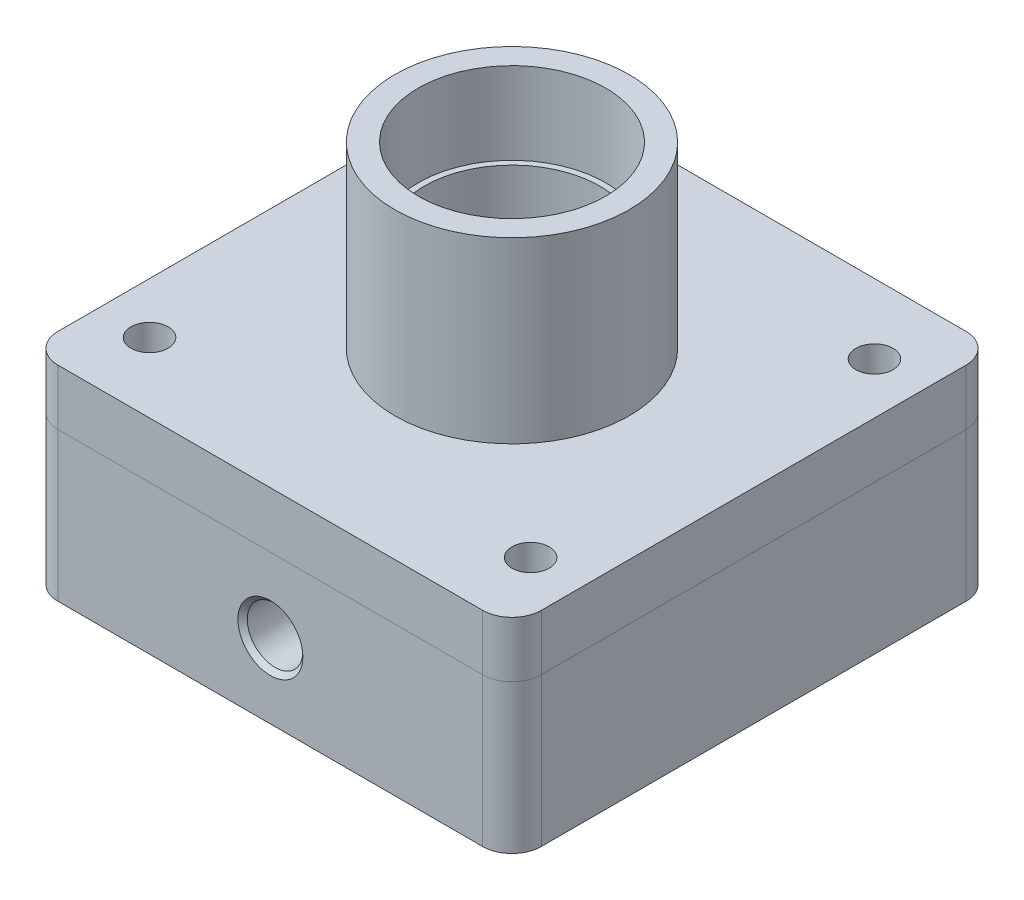
SolidWorks part; units mm, degrees
ref_plane "Front Plane" through (0, 0, 0) normal (0, 0, 1) x (1, 0, 0)
ref_plane "Top Plane" through (0, 0, 0) normal (0, 1, 0) x (1, 0, 0)
ref_plane "Right Plane" through (0, 0, 0) normal (1, 0, 0) x (0, 0, -1)
sketch "Sketch1" plane through (0, 0, 0) normal (0, 1, 0) x (1, 0, 0)
  line L1 (-82.5, 82.5) -> (82.5, 82.5)
  line L2 (-82.5, 82.5) -> (-82.5, -82.5)
  line L3 (-82.5, -82.5) -> (82.5, -82.5)
  line L4 (82.5, 82.5) -> (82.5, -82.5)
  line L5 (-82.5, 82.5) -> (82.5, -82.5) construction
  line L6 (-82.5, -82.5) -> (82.5, 82.5) construction
  point P0 (0, 0)
extrude "Boss-Extrude1" add sketch "Sketch1" along normal blind 50.8
sketch "Sketch2" plane through (0, 50.8, 0) normal (0, 1, 0) x (1, 0, 0)
  circle A0 centre (0, 0) radius 40
extrude "Boss-Extrude2" add sketch "Sketch2" along normal blind 80
sketch "Sketch3" plane through (0, 130.8, 0) normal (0, 1, 0) x (1, 0, 0)
  circle A0 centre (0, 0) radius 32
extrude "Cut-Extrude1" cut sketch "Sketch3" against normal blind 28
sketch "Sketch4" plane through (0, 102.8, 0) normal (0, 1, 0) x (1, 0, 0)
  circle A0 centre (0, 0) radius 30
extrude "Cut-Extrude2" cut sketch "Sketch4" against normal blind 22
fillet "Fillet1" radius 10 4 edges at (82.5, 25.4, 82.5) (-82.5, 25.4, -82.5) (82.5, 25.4, -82.5) (-82.5, 25.4, 82.5)
sketch "Sketch5" plane through (0, 0, 0) normal (0, -1, 0) x (1, 0, 0)
  circle A0 centre (0, 0) radius 20
extrude "Cut-Extrude3" cut sketch "Sketch5" against normal blind 40
sketch "Sketch6" plane through (0, 0, 0) normal (0, -1, 0) x (1, 0, 0)
  circle A0 centre (0, 0) radius 76.2
  circle A1 centre (0, 0) radius 69.85
extrude "Cut-Extrude4" cut sketch "Sketch6" against normal blind 10
sketch "Sketch7" plane through (0, 0, 82.5) normal (0, 0, 1) x (1, 0, 0)
  line L0 (-72.5, 25.4) -> (76.5172, 25.4) construction
  line L1 (-72.5, 50.8) -> (-72.5, 0) construction
sketch "Sketch12" plane through (0, 0, 0) normal (0, -1, 0) x (1, 0, 0)
  line L0 (0, 50.5) -> (0, 82.5)
  line L1 (-72.5, 82.5) -> (76.5172, 82.5) construction
  line L2 (0, 0) -> (0, 50.5)
  circle A0 centre (0, 50.5) radius 6.35
  dimension "D1" = 32
sketch "Sketch16" plane through (0, 0, 82.5) normal (0, 0, 1) x (1, 0, 0)
  line L0 (0, 0) -> (0, 50.8) construction
  line L1 (-72.5, 50.8) -> (72.5, 50.8) construction
hole_wizard "1/2-14 NPSM Tapped Hole2" positions "Sketch18" profile "Sketch19" tap size "1/2-14 NPSM" standard "ANSI Inch"
sketch "Sketch18" plane through (0, 0, 82.5) normal (0, 0, 1) x (1, 0, 0)
  line L0 (0, 0) -> (0, 50.8) construction
  point P0 (0, 25.4)
sketch "Sketch19" plane through (0, 25.4, 82.5) normal (1, 0, 0) x (0, -1, 0)
  line L0 (0, 0) -> (0, 52.9503)
  line L1 (0, 52.9503) -> (9.4869, 47.25)
  line L2 (9.4869, 47.25) -> (9.4869, 1.6002)
  line L3 (9.4869, 1.6002) -> (11.0871, 0)
  line L5 (11.0871, 0) -> (0, 0)
  line L6 (-9.4869, 1.6002) -> (-11.0871, 0) construction
  line L10 (0, 52.9503) -> (-9.4869, 47.25) construction
  line L11 (0, -6.35) -> (0, 107.95) construction
  dimension "Tap Drill Dia." = 18.9738
  dimension "Tap Drill Depth" = 47.25
  dimension "Near C'Sink Dia." = 22.1742
  dimension "Near C'Sink Angle" = 90
  dimension "Drill Angle" = 118
cosmetic thread "Hole Thread2" parameters "D1"=41.81, "D2"=20.9042
extrude "Cut-Extrude5" cut sketch "Sketch12" against normal blind 25 contours A0
sketch "Sketch20" plane through (0, 0, 0) normal (0, -1, 0) x (1, 0, 0)
  line L1 (-65.0558, 58.7091) -> (65.0558, 58.7091) construction
  line L2 (-65.0558, 58.7091) -> (-65.0558, -58.7091) construction
  line L3 (-65.0558, -58.7091) -> (65.0558, -58.7091) construction
  line L4 (65.0558, 58.7091) -> (65.0558, -58.7091) construction
  line L5 (-65.0558, 58.7091) -> (65.0558, -58.7091) construction
  line L6 (-65.0558, -58.7091) -> (65.0558, 58.7091) construction
  circle A0 centre (0, 0) radius 87.63
  circle A1 centre (-65.0558, 58.7091) radius 6.35
  circle A2 centre (-65.0558, -58.7091) radius 6.35
  circle A3 centre (65.0558, -58.7091) radius 6.35
  circle A4 centre (65.0558, 58.7091) radius 6.35
extrude "Cut-Extrude6" cut sketch "Sketch20" against normal through all contours A1 | A3 | A2 | A4
sketch "Sketch24" plane through (0, 50.8, 0) normal (0, 1, 0) x (1, 0, 0)
  line L4 (-72.5, -82.5) -> (72.5, -82.5)
  line L5 (82.5, -72.5) -> (82.5, 72.5)
  line L6 (72.5, 82.5) -> (-72.5, 82.5)
  line L7 (-82.5, 72.5) -> (-82.5, -72.5)
  line L8 (-72.5, -82.5) -> (72.5, -82.5)
  line L9 (82.5, -72.5) -> (82.5, 72.5)
  line L10 (72.5, 82.5) -> (-72.5, 82.5)
  line L11 (-82.5, 72.5) -> (-82.5, -72.5)
  circle A0 centre (-65.0558, -58.7091) radius 6.35 construction
  circle A1 centre (-65.0558, 58.7091) radius 6.35 construction
  circle A2 centre (65.0558, -58.7091) radius 6.35 construction
  circle A3 centre (65.0558, 58.7091) radius 6.35 construction
  arc A4 (72.5, -82.5) -> (82.5, -72.5) centre (72.5, -72.5) ccw
  arc A5 (82.5, 72.5) -> (72.5, 82.5) centre (72.5, 72.5) ccw
  arc A6 (-72.5, 82.5) -> (-82.5, 72.5) centre (-72.5, 72.5) ccw
  arc A7 (-82.5, -72.5) -> (-72.5, -82.5) centre (-72.5, -72.5) ccw
  arc A8 (72.5, -82.5) -> (82.5, -72.5) centre (72.5, -72.5) ccw
  arc A9 (82.5, 72.5) -> (72.5, 82.5) centre (72.5, 72.5) ccw
  arc A10 (-72.5, 82.5) -> (-82.5, 72.5) centre (-72.5, 72.5) ccw
  arc A11 (-82.5, -72.5) -> (-72.5, -82.5) centre (-72.5, -72.5) ccw
  circle A12 centre (-65.0558, -58.7091) radius 6.35
  circle A13 centre (-65.0558, 58.7091) radius 6.35
  circle A14 centre (65.0558, -58.7091) radius 6.35
  circle A15 centre (65.0558, 58.7091) radius 6.35
  dimension "D1" = 0
extrude "Boss-Extrude4" add sketch "Sketch24" along normal blind 19.05 separate body
